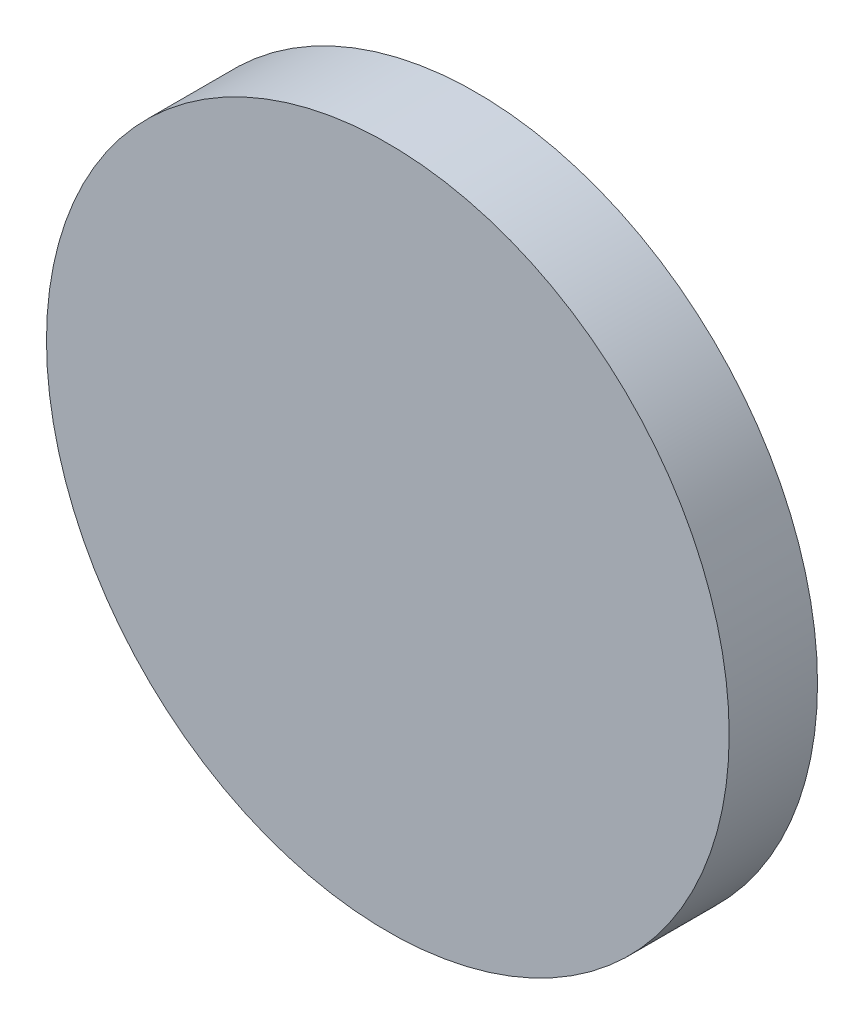
SolidWorks part; units mm, degrees
ref_plane "Front Plane" through (0, 0, 0) normal (0, 0, 1) x (1, 0, 0)
ref_plane "Top Plane" through (0, 0, 0) normal (0, 1, 0) x (1, 0, 0)
ref_plane "Right Plane" through (0, 0, 0) normal (1, 0, 0) x (0, 0, -1)
sketch "Sketch1" plane through (0, 0, 0) normal (0, 0, 1) x (1, 0, 0)
  circle A0 centre (0, 0) radius 80
  dimension "D1" = 160
extrude "Boss-Extrude1" add sketch "Sketch1" along normal blind 20.7
